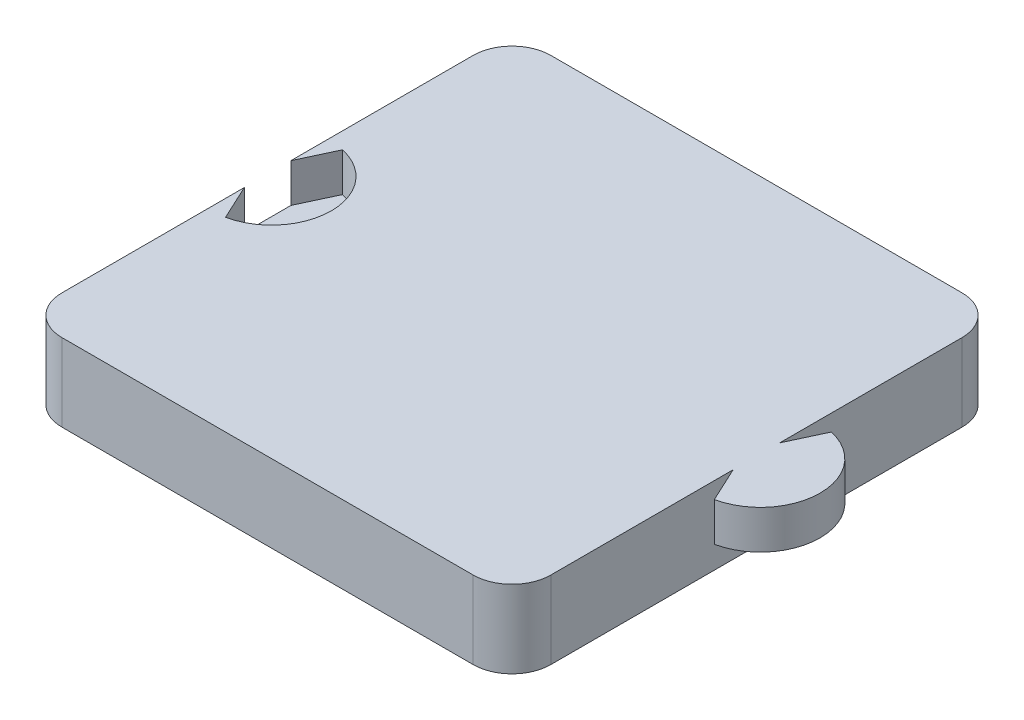
SolidWorks part; units mm, degrees
ref_plane "Front Plane" through (0, 0, 0) normal (0, 0, 1) x (1, 0, 0)
ref_plane "Top Plane" through (0, 0, 0) normal (0, 1, 0) x (1, 0, 0)
ref_plane "Right Plane" through (0, 0, 0) normal (1, 0, 0) x (0, 0, -1)
sketch "Sketch1" plane through (0, 0, 0) normal (0, 1, 0) x (1, 0, 0)
  line L1 (-33.655, -40.005) -> (33.655, -40.005)
  line L2 (-40.005, -33.655) -> (-40.005, 33.655)
  line L3 (-33.655, 40.005) -> (33.655, 40.005)
  line L4 (40.005, -33.655) -> (40.005, 33.655)
  line L5 (-40.005, -40.005) -> (40.005, 40.005) construction
  line L6 (-40.005, 40.005) -> (40.005, -40.005) construction
  arc A0 (-40.005, 33.655) -> (-33.655, 40.005) centre (-33.655, 33.655) cw
  arc A1 (33.655, -40.005) -> (40.005, -33.655) centre (33.655, -33.655) ccw
  arc A2 (-33.655, -40.005) -> (-40.005, -33.655) centre (-33.655, -33.655) cw
  arc A3 (33.655, 40.005) -> (40.005, 33.655) centre (33.655, 33.655) cw
  point P0 (0, 0)
  dimension "D1" = 6.35
  dimension "D2" = 6.35
  dimension "D3" = 80.01
extrude "Boss-Extrude1" add sketch "Sketch1" along normal blind 12.7
sketch "Sketch2" plane through (0, 12.7, 0) normal (0, 1, 0) x (1, 0, 0)
  line L0 (0, 0) -> (-40.005, 0) construction
  line L1 (-40.005, 33.655) -> (-40.005, -33.655) construction
  line L2 (-40.005, 3.81) -> (-30.5237, 24.1426) construction
  line L3 (-40.005, 3.81) -> (-37.3214, 9.5651)
  line L4 (-40.005, 0) -> (-32.385, 0) construction
  line L5 (-40.005, 3.81) -> (-40.005, -3.81)
  line L6 (-40.005, -3.81) -> (-37.3214, -9.5651)
  arc A0 (-37.3214, 9.5651) -> (-37.3214, -9.5651) centre (-39.3557, 0) cw
  dimension "D3" = 6.35
  dimension "D4" = 7.62
  dimension "D5" = 9.779
  dimension "D1" = 25
  dimension "D2" = 3.81
extrude "Cut-Extrude1" cut sketch "Sketch2" against normal blind 6.35
sketch "Sketch4" plane through (0, 12.7, 0) normal (0, 1, 0) x (1, 0, 0)
  line L6 (42.6886, 9.5651) -> (40.005, 3.81)
  line L7 (40.005, 3.81) -> (40.005, -3.81)
  line L8 (40.005, -3.81) -> (42.6886, -9.5651)
  arc A2 (42.6886, -9.5651) -> (42.6886, 9.5651) centre (40.6543, 0) ccw
extrude "Boss-Extrude2" add sketch "Sketch4" against normal blind 6.35
